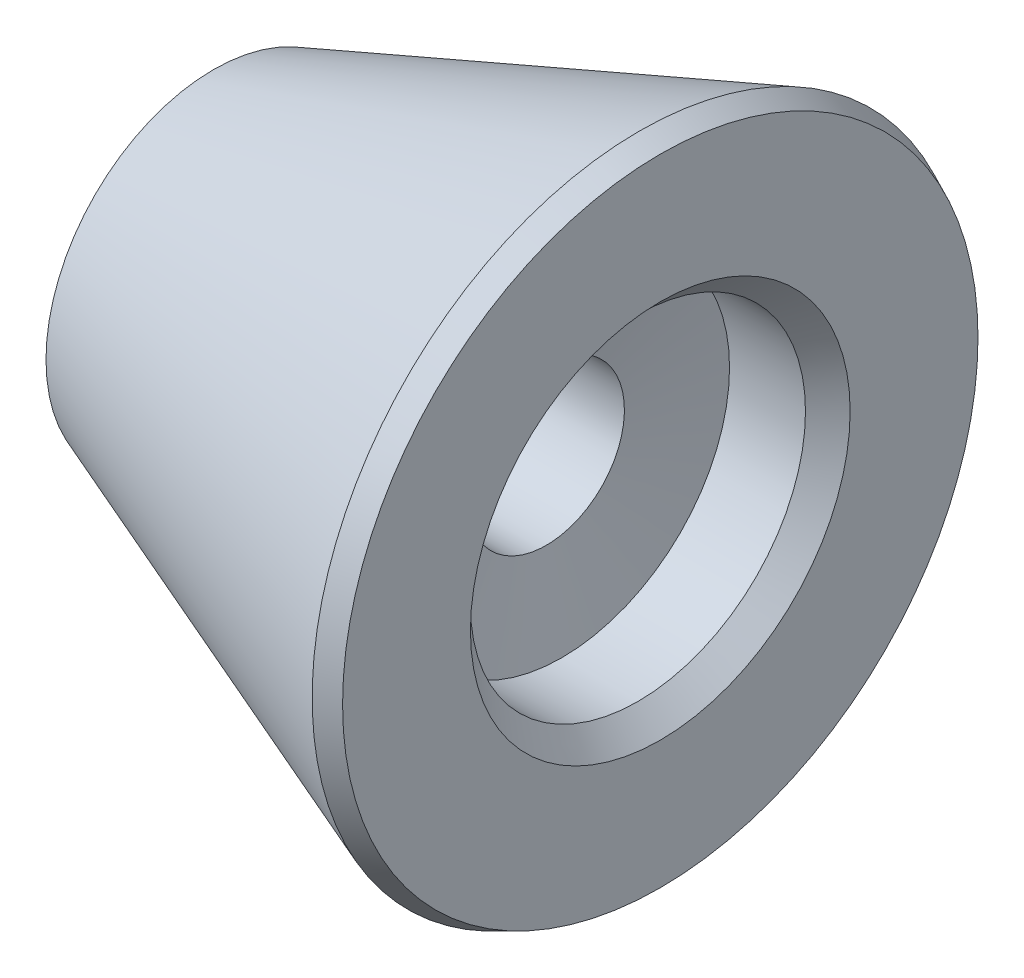
SolidWorks part; units mm, degrees
ref_plane "Alzado" through (0, 0, 0) normal (1, 0, 0) x (0, 1, 0)
ref_plane "Planta" through (0, 0, 0) normal (0, 0, 1) x (0, 1, 0)
ref_plane "Vista lateral" through (0, 0, 0) normal (0, 1, 0) x (-1, 0, 0)
sketch "Croquis1" plane through (0, 0, 0) normal (0, 0, 1) x (0, 1, 0)
  line L0 (0, 0) -> (0, 10) construction
  line L1 (0, 0) -> (15, 0) construction
  line L2 (7.5, -10) -> (15, -10)
  line L3 (15, -10) -> (7.5, 10)
  line L4 (7.5, -10) -> (7.5, -5.6)
  line L6 (3.5, 10) -> (7.5, 10)
  line L7 (7.5, -5.6) -> (3.5, -4.8947)
  line L8 (3.5, -4.8947) -> (3.5, 10)
  dimension "D1" = 10
  dimension "D2" = 15
  dimension "D3" = 15
  dimension "D4" = 4.4
  dimension "D5" = 10
  dimension "D6" = 3.5
  dimension "D7" = 10
revolve "Revolución1" add sketch "Croquis1" angle 360 about L0
sketch "Croquis2" plane through (-10, 0, 0) normal (-1, 0, 0) x (0, -1, 0)
  line L0 (0, 0) -> (23.931, 0) construction
  line L1 (3.06, -5.3) -> (6.1199, 0)
  line L2 (6.1199, 0) -> (3.06, 5.3)
  line L3 (3.06, 5.3) -> (-3.06, 5.3)
  line L4 (-3.06, 5.3) -> (-6.1199, 0)
  line L5 (-6.1199, 0) -> (-3.06, -5.3)
  line L6 (-3.06, -5.3) -> (3.06, -5.3)
  circle A0 centre (0, 0) radius 5.3 construction
  circle A1 centre (0, 0) radius 3.5 construction
  dimension "D1" = 10.6
extrude "Cortar-Extruir1" cut sketch "Croquis2" against normal blind 5.2
chamfer "Chaflán1" distance 1 angle 45 2 edges at (10, 7.5, 0) (10, 15, 0)
